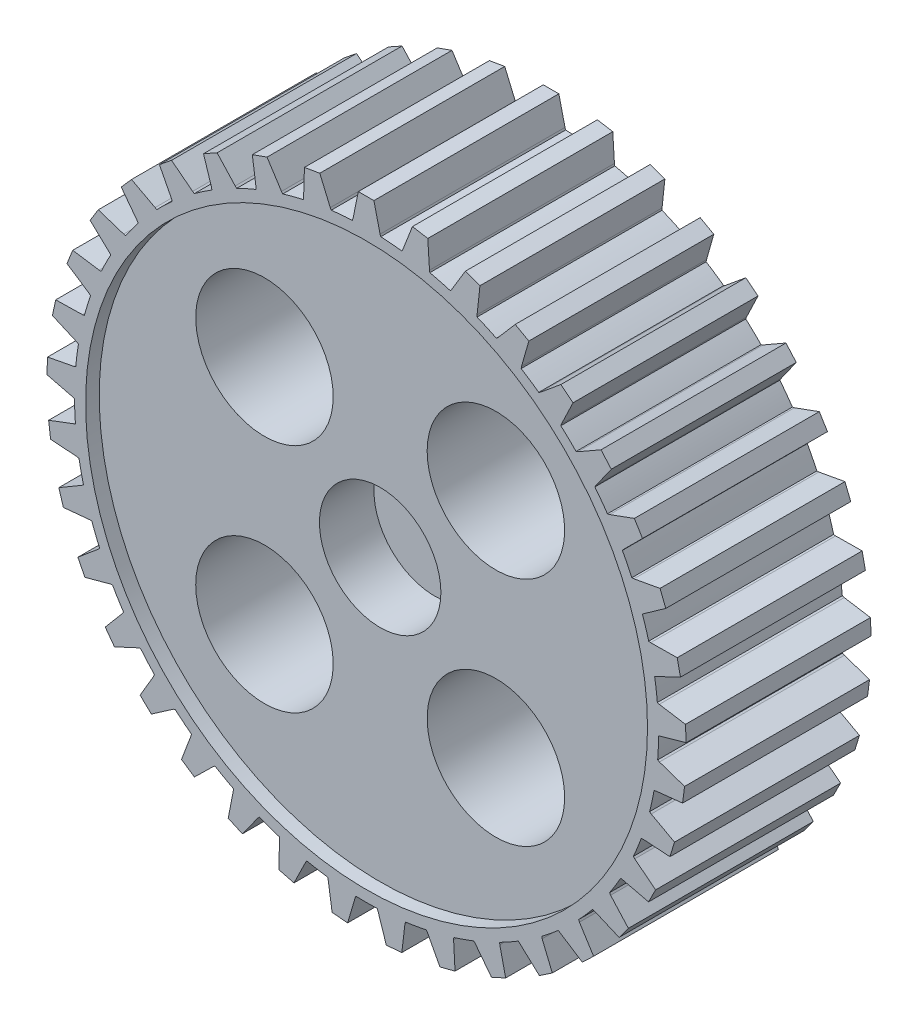
SolidWorks part; units mm, degrees
ref_plane "Front Plane" through (0, 0, 0) normal (0, 0, 1) x (1, 0, 0)
ref_plane "Top Plane" through (0, 0, 0) normal (0, 1, 0) x (1, 0, 0)
ref_plane "Right Plane" through (0, 0, 0) normal (1, 0, 0) x (0, 0, -1)
sketch "Sketch1" plane through (0, 0, 0) normal (0, 0, 1) x (1, 0, 0)
  line L0 (0, 150.7934) -> (0, 127.4203) construction
  line L2 (-6.9497, 150.7934) -> (-4.2214, 164.1484)
  line L3 (6.9497, 150.7934) -> (3.7786, 164.1484)
  line L4 (-6.9497, 150.7934) -> (-7.3096, 149.8218)
  line L5 (6.9497, 150.7934) -> (7.2816, 149.8232)
  line L6 (-4.2214, 164.1484) -> (3.7786, 164.1484)
  line L7 (18.6344, 149.7988) -> (23.5805, 162.5007)
  line L8 (32.334, 147.4498) -> (31.4655, 161.1487)
  line L9 (32.334, 147.4498) -> (32.4971, 146.4375)
  line L10 (18.6344, 149.7988) -> (18.1155, 148.9021)
  line L11 (23.5805, 162.5007) -> (31.4655, 161.1487)
  line L12 (43.6825, 144.4949) -> (50.7041, 156.1782)
  line L13 (56.788, 139.8644) -> (58.2471, 153.513)
  line L14 (56.788, 139.8644) -> (56.7777, 138.8391)
  line L15 (43.6825, 144.4949) -> (43.0195, 143.6987)
  line L16 (50.7041, 156.1782) -> (58.2471, 153.513)
  line L17 (67.474, 135.0341) -> (76.369, 145.3626)
  line L18 (79.6084, 128.2554) -> (83.3531, 141.4611)
  line L19 (79.6084, 128.2554) -> (79.425, 127.2465)
  line L20 (67.474, 135.0341) -> (66.6859, 134.3614)
  line L21 (76.369, 145.3626) -> (83.3531, 141.4611)
  line L22 (89.3243, 121.6886) -> (99.8369, 130.3653)
  line L23 (100.1385, 112.9567) -> (106.0612, 125.3395)
  line L24 (100.1385, 112.9567) -> (99.7873, 111.9933)
  line L25 (89.3243, 121.6886) -> (88.4339, 121.1588)
  line L26 (99.8369, 130.3653) -> (106.0612, 125.3395)
  line L27 (108.6049, 104.8423) -> (120.4327, 111.6176)
  line L28 (117.7879, 94.4084) -> (125.7181, 105.6122)
  line L29 (117.7879, 94.4084) -> (117.2789, 93.5182)
  line L30 (108.6049, 104.8423) -> (107.6378, 104.4706)
  line L31 (120.4327, 111.6176) -> (125.7181, 105.6122)
  line L32 (124.7612, 84.9799) -> (137.5639, 89.6588)
  line L33 (132.0487, 73.1442) -> (141.7583, 82.8466)
  line L34 (132.0487, 73.1442) -> (131.3966, 72.3528)
  line L35 (124.7612, 84.9799) -> (123.7451, 84.777)
  line L36 (137.5639, 89.6588) -> (141.7583, 82.8466)
  line L37 (137.3283, 62.6729) -> (150.7375, 65.1208)
  line L38 (142.5108, 49.7757) -> (153.7204, 57.6977)
  line L39 (142.5108, 49.7757) -> (141.7343, 49.106)
  line L40 (137.3283, 62.6729) -> (136.2925, 62.6446)
  line L41 (150.7375, 65.1208) -> (153.7204, 57.6977)
  line L42 (145.9447, 38.5628) -> (159.5748, 38.7093)
  line L43 (148.873, 24.9753) -> (161.2602, 30.8889)
  line L44 (148.873, 24.9753) -> (147.9945, 24.4464)
  line L45 (145.9447, 38.5628) -> (144.9191, 38.7099)
  line L46 (159.5748, 38.7093) -> (161.2602, 30.8889)
  line L47 (150.3625, 13.3433) -> (163.8214, 11.1842)
  line L48 (150.9524, -0.5436) -> (164.1609, 3.1914)
  line L49 (150.9524, -0.5436) -> (149.9972, -0.9164)
  line L50 (150.3625, 13.3433) -> (149.3766, 13.6617)
  line L51 (163.8214, 11.1842) -> (164.1609, 3.1914)
  line L52 (150.4547, -12.26) -> (163.3551, -16.6626)
  line L53 (148.6893, -26.0469) -> (162.3389, -24.5978)
  line L54 (148.6893, -26.0469) -> (147.6848, -26.2529)
  line L55 (150.4547, -12.26) -> (149.5368, -11.7796)
  line L56 (163.3551, -16.6626) -> (162.3389, -24.5978)
  line L57 (146.2186, -37.5106) -> (158.1894, -44.03)
  line L58 (142.1486, -50.8008) -> (155.8468, -51.6794)
  line L59 (142.1486, -50.8008) -> (141.1237, -50.8341)
  line L60 (146.2186, -37.5106) -> (145.395, -36.882)
  line L61 (158.1894, -44.03) -> (155.8468, -51.6794)
  line L62 (137.7761, -61.6821) -> (148.4729, -70.1308)
  line L63 (131.5185, -74.0933) -> (144.8712, -77.2743)
  line L64 (131.5185, -74.0933) -> (130.5027, -73.9529)
  line L65 (137.7761, -61.6821) -> (137.0706, -60.9234)
  line L66 (148.4729, -70.1308) -> (144.8712, -77.2743)
  line L67 (125.37, -84.0792) -> (134.485, -94.2141)
  line L68 (117.1049, -95.2543) -> (129.728, -100.6461)
  line L69 (117.1049, -95.2543) -> (116.1275, -94.9442)
  line L70 (125.37, -84.0792) -> (124.8028, -83.2121)
  line L71 (134.485, -94.2141) -> (129.728, -100.6461)
  line L72 (109.3572, -104.0574) -> (116.6283, -115.587)
  line L73 (99.3224, -113.675) -> (110.8527, -121.1225)
  line L74 (99.3224, -113.675) -> (98.4114, -113.2042)
  line L75 (109.3572, -104.0574) -> (108.9448, -103.1069)
  line L76 (116.6283, -115.587) -> (110.8527, -121.1225)
  line L77 (90.1984, -121.0421) -> (95.4164, -133.6347)
  line L78 (78.6826, -128.8254) -> (88.7884, -138.1145)
  line L79 (78.6826, -128.8254) -> (77.8643, -128.2075)
  line L80 (90.1984, -121.0421) -> (89.9525, -120.0356)
  line L81 (95.4164, -133.6347) -> (88.7884, -138.1145)
  line L82 (68.4448, -134.5446) -> (71.4596, -147.8379)
  line L83 (55.7792, -140.2698) -> (64.1698, -151.1331)
  line L84 (55.7792, -140.2698) -> (55.0771, -139.5224)
  line L85 (68.4448, -134.5446) -> (68.3725, -133.511)
  line L86 (71.4596, -147.8379) -> (64.1698, -151.1331)
  line L87 (44.7221, -144.1765) -> (45.447, -157.7881)
  line L88 (31.2711, -147.6789) -> (37.7051, -159.804)
  line L89 (31.2711, -147.6789) -> (30.7055, -146.8236)
  line L90 (44.7221, -144.1765) -> (44.8256, -143.1456)
  line L91 (45.447, -157.7881) -> (37.7051, -159.804)
  line L92 (19.7129, -149.6607) -> (18.1269, -163.1991)
  line L93 (5.8635, -150.8395) -> (10.1558, -163.8775)
  line L94 (5.8635, -150.8395) -> (5.4505, -149.9009)
  line L95 (19.7129, -149.6607) -> (19.9891, -148.6622)
  line L96 (18.1269, -163.1991) -> (10.1558, -163.8775)
  line L97 (-5.8635, -150.8395) -> (-9.7146, -163.9151)
  line L98 (-19.7129, -149.6607) -> (-17.6858, -163.2366)
  line L99 (-19.7129, -149.6607) -> (-19.9613, -148.6659)
  line L100 (-5.8635, -150.8395) -> (-5.4225, -149.902)
  line L101 (-9.7146, -163.9151) -> (-17.6858, -163.2366)
  line L102 (-31.2711, -147.6789) -> (-37.2766, -159.9155)
  line L103 (-44.7221, -144.1765) -> (-45.0185, -157.8997)
  line L104 (-44.7221, -144.1765) -> (-44.7988, -143.154)
  line L105 (-31.2711, -147.6789) -> (-30.678, -146.8294)
  line L106 (-37.2766, -159.9155) -> (-45.0185, -157.8997)
  line L107 (-55.7792, -140.2698) -> (-63.7663, -151.3155)
  line L108 (-68.4448, -134.5446) -> (-71.0561, -148.0203)
  line L109 (-68.4448, -134.5446) -> (-68.3476, -133.5238)
  line L110 (-55.7792, -140.2698) -> (-55.051, -139.5327)
  line L111 (-63.7663, -151.3155) -> (-71.0561, -148.0203)
  line L112 (-78.6826, -128.8254) -> (-88.4215, -138.3624)
  line L113 (-90.1984, -121.0421) -> (-95.0496, -133.8826)
  line L114 (-90.1984, -121.0421) -> (-89.9301, -120.0524)
  line L115 (-78.6826, -128.8254) -> (-77.8403, -128.222)
  line L116 (-88.4215, -138.3624) -> (-95.0496, -133.8826)
  line L117 (-99.3224, -113.675) -> (-110.533, -121.4289)
  line L118 (-109.3572, -104.0574) -> (-116.3087, -115.8934)
  line L119 (-109.3572, -104.0574) -> (-108.9255, -103.1273)
  line L120 (-99.3224, -113.675) -> (-98.3903, -113.2226)
  line L121 (-110.533, -121.4289) -> (-116.3087, -115.8934)
  line L122 (-117.1049, -95.2543) -> (-129.4647, -101.0021)
  line L123 (-125.37, -84.0792) -> (-134.2217, -94.5701)
  line L124 (-125.37, -84.0792) -> (-124.7873, -83.2354)
  line L125 (-117.1049, -95.2543) -> (-116.1097, -94.9659)
  line L126 (-129.4647, -101.0021) -> (-134.2217, -94.5701)
  line L127 (-131.5185, -74.0933) -> (-144.6719, -77.6696)
  line L128 (-137.7761, -61.6821) -> (-148.2735, -70.5262)
  line L129 (-137.7761, -61.6821) -> (-137.0592, -60.949)
  line L130 (-131.5185, -74.0933) -> (-130.4889, -73.9773)
  line L131 (-144.6719, -77.6696) -> (-148.2735, -70.5262)
  line L132 (-142.1486, -50.8008) -> (-155.7171, -52.1027)
  line L133 (-146.2186, -37.5106) -> (-158.0597, -44.4534)
  line L134 (-146.2186, -37.5106) -> (-145.3881, -36.9092)
  line L135 (-142.1486, -50.8008) -> (-141.1142, -50.8605)
  line L136 (-155.7171, -52.1027) -> (-158.0597, -44.4534)
  line L137 (-148.6893, -26.0469) -> (-162.2827, -25.037)
  line L138 (-150.4547, -12.26) -> (-163.2988, -17.1018)
  line L139 (-150.4547, -12.26) -> (-149.5346, -11.8076)
  line L140 (-148.6893, -26.0469) -> (-147.6798, -26.2805)
  line L141 (-162.2827, -25.037) -> (-163.2988, -17.1018)
  line L142 (-150.9524, -0.5436) -> (-164.1797, 2.7491)
  line L143 (-150.3625, 13.3433) -> (-163.8401, 10.7419)
  line L144 (-150.3625, 13.3433) -> (-149.3791, 13.6338)
  line L145 (-150.9524, -0.5436) -> (-149.997, -0.9444)
  line L146 (-164.1797, 2.7491) -> (-163.8401, 10.7419)
  line L147 (-148.873, 24.9753) -> (-161.3535, 30.456)
  line L148 (-145.9447, 38.5628) -> (-159.6681, 38.2765)
  line L149 (-145.9447, 38.5628) -> (-144.9263, 38.6828)
  line L150 (-148.873, 24.9753) -> (-147.9991, 24.4188)
  line L151 (-161.3535, 30.456) -> (-159.6681, 38.2765)
  line L152 (-142.5108, 49.7757) -> (-153.8855, 57.2868)
  line L153 (-137.3283, 62.6729) -> (-150.9026, 64.7099)
  line L154 (-137.3283, 62.6729) -> (-136.3043, 62.6191)
  line L155 (-142.5108, 49.7757) -> (-141.7434, 49.0795)
  line L156 (-153.8855, 57.2868) -> (-150.9026, 64.7099)
  line L157 (-132.0487, 73.1442) -> (-141.9905, 82.4696)
  line L158 (-124.7612, 84.9799) -> (-137.796, 89.2818)
  line L159 (-124.7612, 84.9799) -> (-123.761, 84.7539)
  line L160 (-132.0487, 73.1442) -> (-131.4101, 72.3283)
  line L161 (-141.9905, 82.4696) -> (-137.796, 89.2818)
  line L162 (-117.7879, 94.4084) -> (-126.0106, 105.2798)
  line L163 (-108.6049, 104.8423) -> (-120.7252, 111.2852)
  line L164 (-108.6049, 104.8423) -> (-107.6573, 104.4505)
  line L165 (-117.7879, 94.4084) -> (-117.2964, 93.4963)
  line L166 (-126.0106, 105.2798) -> (-120.7252, 111.2852)
  line L167 (-100.1385, 112.9567) -> (-106.4057, 125.0614)
  line L168 (-89.3243, 121.6886) -> (-100.1814, 130.0871)
  line L169 (-89.3243, 121.6886) -> (-88.4565, 121.1422)
  line L170 (-100.1385, 112.9567) -> (-99.8082, 111.9746)
  line L171 (-106.4057, 125.0614) -> (-100.1814, 130.0871)
  line L172 (-79.6084, 128.2554) -> (-83.7397, 141.2451)
  line L173 (-67.474, 135.0341) -> (-76.7556, 145.1467)
  line L174 (-67.474, 135.0341) -> (-66.711, 134.3489)
  line L175 (-79.6084, 128.2554) -> (-79.4488, 127.2317)
  line L176 (-83.7397, 141.2451) -> (-76.7556, 145.1467)
  line L177 (-56.788, 139.8644) -> (-58.6646, 153.3655)
  line L178 (-43.6825, 144.4949) -> (-51.1216, 156.0306)
  line L179 (-43.6825, 144.4949) -> (-43.0464, 143.6907)
  line L180 (-56.788, 139.8644) -> (-56.8037, 138.8285)
  line L181 (-58.6646, 153.3655) -> (-51.1216, 156.0306)
  line L182 (-32.334, 147.4498) -> (-31.9019, 161.0739)
  line L183 (-18.6344, 149.7988) -> (-24.017, 162.4259)
  line L184 (-18.6344, 149.7988) -> (-18.1433, 148.8987)
  line L185 (-32.334, 147.4498) -> (-32.5245, 146.4314)
  line L186 (-31.9019, 161.0739) -> (-24.017, 162.4259)
  arc A0 (-7.3096, 149.8218) -> (-18.1433, 148.8987) centre (0, 0) ccw
  arc A1 (18.1155, 148.9021) -> (7.2816, 149.8232) centre (0, 0) ccw
  arc A2 (43.0195, 143.6987) -> (32.4971, 146.4375) centre (0, 0) ccw
  arc A3 (66.6859, 134.3614) -> (56.7777, 138.8391) centre (0, 0) ccw
  arc A4 (88.4339, 121.1588) -> (79.425, 127.2465) centre (0, 0) ccw
  arc A5 (107.6378, 104.4706) -> (99.7873, 111.9933) centre (0, 0) ccw
  arc A6 (136.2925, 62.6446) -> (131.3966, 72.3528) centre (0, 0) ccw
  arc A7 (123.7451, 84.777) -> (117.2789, 93.5182) centre (0, 0) ccw
  arc A8 (144.9191, 38.7099) -> (141.7343, 49.106) centre (0, 0) ccw
  arc A9 (149.3766, 13.6617) -> (147.9945, 24.4464) centre (0, 0) ccw
  arc A10 (137.0706, -60.9234) -> (141.1237, -50.8341) centre (0, 0) ccw
  arc A11 (145.395, -36.882) -> (147.6848, -26.2529) centre (0, 0) ccw
  arc A12 (149.5368, -11.7796) -> (149.9972, -0.9164) centre (0, 0) ccw
  arc A13 (124.8028, -83.2121) -> (130.5027, -73.9529) centre (0, 0) ccw
  arc A14 (108.9448, -103.1069) -> (116.1275, -94.9442) centre (0, 0) ccw
  arc A15 (89.9525, -120.0356) -> (98.4114, -113.2042) centre (0, 0) ccw
  arc A16 (68.3725, -133.511) -> (77.8643, -128.2075) centre (0, 0) ccw
  arc A17 (19.9891, -148.6622) -> (30.7055, -146.8236) centre (0, 0) ccw
  arc A18 (44.8256, -143.1456) -> (55.0771, -139.5224) centre (0, 0) ccw
  arc A19 (-5.4225, -149.902) -> (5.4505, -149.9009) centre (0, 0) ccw
  arc A20 (-30.678, -146.8294) -> (-19.9613, -148.6659) centre (0, 0) ccw
  arc A21 (-55.051, -139.5327) -> (-44.7988, -143.154) centre (0, 0) ccw
  arc A22 (-77.8403, -128.222) -> (-68.3476, -133.5238) centre (0, 0) ccw
  arc A23 (-98.3903, -113.2226) -> (-89.9301, -120.0524) centre (0, 0) ccw
  arc A24 (-116.1097, -94.9659) -> (-108.9255, -103.1273) centre (0, 0) ccw
  arc A25 (-130.4889, -73.9773) -> (-124.7873, -83.2354) centre (0, 0) ccw
  arc A26 (-141.1142, -50.8605) -> (-137.0592, -60.949) centre (0, 0) ccw
  arc A27 (-147.6798, -26.2805) -> (-145.3881, -36.9092) centre (0, 0) ccw
  arc A28 (-149.997, -0.9444) -> (-149.5346, -11.8076) centre (0, 0) ccw
  arc A29 (-147.9991, 24.4188) -> (-149.3791, 13.6338) centre (0, 0) ccw
  arc A30 (-141.7434, 49.0795) -> (-144.9263, 38.6828) centre (0, 0) ccw
  arc A31 (-131.4101, 72.3283) -> (-136.3043, 62.6191) centre (0, 0) ccw
  arc A32 (-117.2964, 93.4963) -> (-123.761, 84.7539) centre (0, 0) ccw
  arc A33 (-99.8082, 111.9746) -> (-107.6573, 104.4505) centre (0, 0) ccw
  arc A34 (-79.4488, 127.2317) -> (-88.4565, 121.1422) centre (0, 0) ccw
  arc A35 (-56.8037, 138.8285) -> (-66.711, 134.3489) centre (0, 0) ccw
  arc A36 (-32.5245, 146.4314) -> (-43.0464, 143.6907) centre (0, 0) ccw
  point P228 (0, 0)
  dimension "D1" = 300
  dimension "D2" = 8
  dimension "D3" = 37
extrude "Boss-Extrude1" add sketch "Sketch1" along normal blind 95
sketch "Sketch2" plane through (0, 0, 95) normal (0, 0, 1) x (1, 0, 0)
  circle A0 centre (0, 0) radius 144.3236
extrude "Cut-Extrude1" cut sketch "Sketch2" against normal blind 7
sketch "Sketch3" plane through (0, 0, 88) normal (0, 0, 1) x (1, 0, 0)
  line L0 (0, 144.3236) -> (0, -144.3236) construction
  line L1 (-144.3236, 0) -> (144.3236, 0) construction
  circle A0 centre (0, 0) radius 144.3236 construction
  circle A1 centre (0, 0) radius 144.3236 construction
  circle A2 centre (-59.4417, 59.4417) radius 35.3089
  circle A3 centre (-59.4417, -59.4417) radius 35.3089
  circle A4 centre (59.4417, -59.4417) radius 35.3089
  circle A5 centre (59.4417, 59.4417) radius 35.3089
  point P11 (0, 0)
  point P15 (-59.4417, 59.4417)
extrude "Cut-Extrude2" cut sketch "Sketch3" against normal blind 547
sketch "Sketch4" plane through (0, 0, 88) normal (0, 0, 1) x (1, 0, 0)
  circle A0 centre (0, 0) radius 25.127
extrude "Boss-Extrude2" add sketch "Sketch4" against normal blind 31
sketch "Sketch5" plane through (0, 0, 0) normal (0, 0, -1) x (-1, 0, 0)
  circle A0 centre (0, 0) radius 141.9442
extrude "Cut-Extrude3" cut sketch "Sketch5" against normal blind 7
sketch "Sketch7" plane through (0, 0, 7) normal (0, 0, -1) x (-1, 0, 0)
  circle A0 centre (0, 0) radius 30.7656
extrude "Cut-Extrude4" cut sketch "Sketch7" against normal blind 28
sketch "Sketch8" plane through (0, 0, 88) normal (0, 0, 1) x (1, 0, 0)
  circle A0 centre (0, 0) radius 31.1916
extrude "Cut-Extrude5" cut sketch "Sketch8" against normal blind 28
